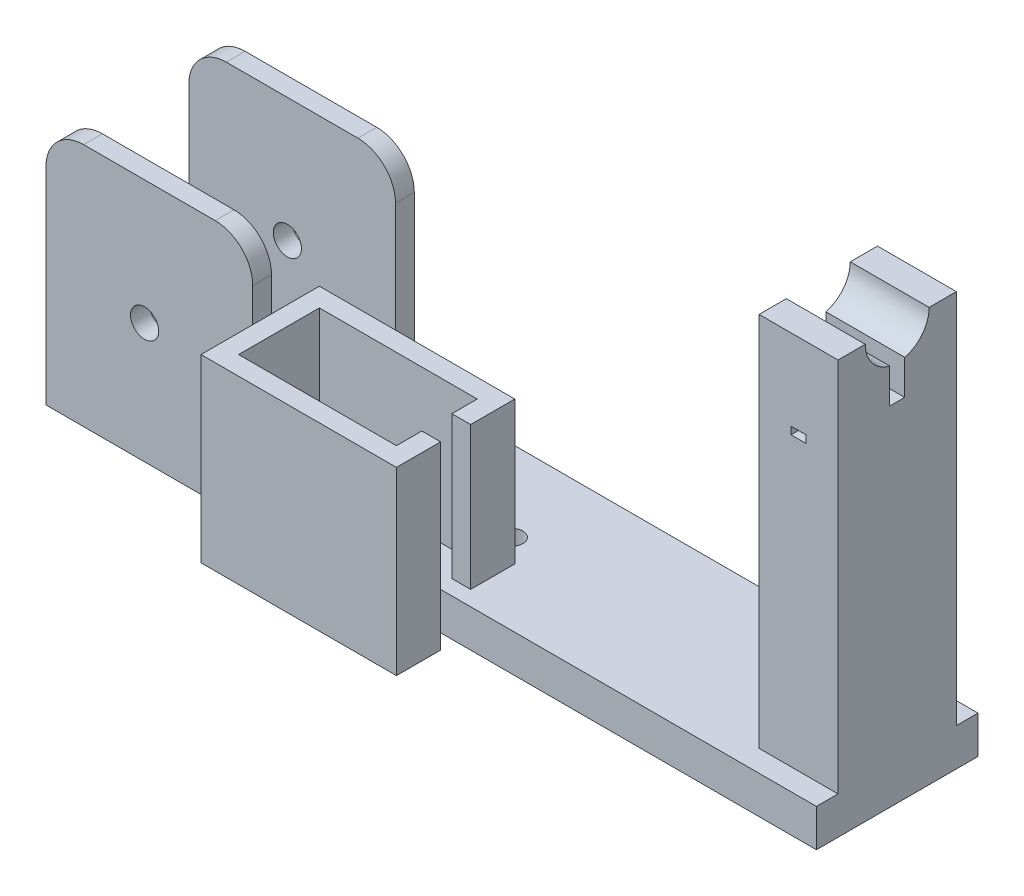
SolidWorks part; units mm, degrees
ref_plane "Front Plane" through (0, 0, 0) normal (0, 0, 1) x (1, 0, 0)
ref_plane "Top Plane" through (0, 0, 0) normal (0, 1, 0) x (1, 0, 0)
ref_plane "Right Plane" through (0, 0, 0) normal (1, 0, 0) x (0, 0, -1)
sketch "Sketch1" plane through (0, 0, 0) normal (0, 1, 0) x (1, 0, 0)
  line L0 (-156.8835, 43.5644) -> (48.1165, 43.5644)
  line L1 (48.1165, 0.5644) -> (-156.8835, 0.5644)
  line L19 (-156.8835, 43.5644) -> (-156.8835, 0.5644)
  line L21 (48.1165, 43.5644) -> (48.1165, 0.5644)
  dimension "D1" = 205
  dimension "D5" = 43
extrude "Boss-Extrude1" add sketch "Sketch1" along normal blind 10
sketch "Sketch2" plane through (0, 0, 0) normal (0, -1, 0) x (1, 0, 0)
  line L0 (-55.6367, -6.8112) -> (-28.1303, -6.8112) construction
  line L1 (-41.8835, -6.8112) -> (-41.8835, -34.3177) construction
  line L2 (-28.1303, -34.3177) -> (-55.6367, -34.3177) construction
  line L3 (-28.1303, -6.8112) -> (-28.1303, -34.3177) construction
  line L4 (-49.4902, -19.0389) -> (-43.4091, -12.9578) construction
  line L5 (-55.6367, -6.8112) -> (-28.1303, -34.3177) construction
  line L6 (-95.1644, -20.5644) -> (-28.1303, -20.5644) construction
  line L7 (-27.868, -10.4768) -> (-34.2768, -19.0389)
  line L8 (-31.7959, -6.5489) -> (-40.358, -12.9578)
  line L9 (-34.2768, -19.0389) -> (-40.358, -12.9578) construction
  line L10 (-55.899, -30.6521) -> (-49.4902, -22.09)
  line L11 (-51.9712, -34.5799) -> (-43.4091, -28.1711)
  line L12 (-51.9712, -6.5489) -> (-43.4091, -12.9578)
  line L13 (-55.899, -10.4768) -> (-49.4902, -19.0389)
  line L14 (-55.6367, -34.3177) -> (-28.1303, -6.8112) construction
  line L15 (-31.7959, -34.5799) -> (-40.358, -28.1711)
  line L16 (-27.868, -30.6521) -> (-34.2768, -22.09)
  line L17 (-156.8835, -0.5644) -> (48.1165, -0.5644) construction
  line L18 (-156.8835, -43.5644) -> (-156.8835, -0.5644) construction
  circle A0 centre (-41.8835, -20.5644) radius 6.75 construction
  arc A1 (-49.4902, -19.0389) -> (-49.4902, -22.09) centre (-50.4202, -20.5644) cw
  arc A2 (-27.868, -30.6521) -> (-31.7959, -34.5799) centre (-30.1144, -32.3335) cw
  arc A3 (-55.899, -10.4768) -> (-51.9712, -6.5489) centre (-53.6526, -8.7953) cw
  arc A4 (-27.868, -10.4768) -> (-31.7959, -6.5489) centre (-30.1144, -8.7953) ccw
  arc A5 (-34.2768, -19.0389) -> (-34.2768, -22.09) centre (-33.3468, -20.5644) ccw
  arc A6 (-55.899, -30.6521) -> (-51.9712, -34.5799) centre (-53.6526, -32.3335) ccw
  arc A7 (-40.358, -28.1711) -> (-43.4091, -28.1711) centre (-41.8835, -29.1011) ccw
  arc A8 (-40.358, -12.9578) -> (-43.4091, -12.9578) centre (-41.8835, -12.0277) cw
  point P6 (-28.1303, -20.5644)
  point P7 (-41.8835, -6.8112)
  dimension "D1" = 19.45
  dimension "D2" = 8.6
  dimension "D3" = 20
  dimension "D4" = 115
extrude "Servo Cutout" [suppressed] cut sketch "Sketch2" against normal blind 3
sketch "Sketch4" plane through (0, 10, 0) normal (0, 1, 0) x (1, 0, 0)
  line L1 (-156.8835, 0.5644) -> (-101.8835, 0.5644)
  line L2 (-156.8835, 0.5644) -> (-156.8835, 5.5644)
  line L3 (-156.8835, 5.5644) -> (-101.8835, 5.5644)
  line L4 (-101.8835, 0.5644) -> (-101.8835, 5.5644)
  dimension "D1" = 55
  dimension "D2" = 5
extrude "Boss-Extrude2" add sketch "Sketch4" along normal blind 55
ref_plane "Plane2" through (0, 0, -22.0644) normal (0, 0, 1) x (1, 0, 0)
mirror "Mirror1" about plane through (0, 0, -22.0644) normal (0, 0, 1) of "Boss-Extrude2"
sketch "Sketch5" plane through (0, 10, 0) normal (0, 1, 0) x (1, 0, 0)
  line L0 (27.1165, 22.0644) -> (48.1165, 22.0644) construction
  line L1 (-35.75, 22.0644) -> (35.75, 22.0644) construction
  line L6 (27.1165, 37.8144) -> (48.1165, 37.8144)
  line L7 (27.1165, 37.8144) -> (27.1165, 6.3144)
  line L13 (27.1165, 6.3144) -> (48.1165, 6.3144)
  line L14 (48.1165, 37.8144) -> (48.1165, 6.3144)
  line L15 (48.1165, 0.5644) -> (48.1165, 43.5644) construction
  point P0 (50.1546, 22.0644)
  dimension "D1" = 0
  dimension "D2" = 0
  dimension "D3" = 21
  dimension "D4" = 31.5
extrude "Barrel Stand" add sketch "Sketch5" along normal blind 100
sketch "Sketch6" plane through (48.1165, 0, 10.3021) normal (-1, 0, 0) x (0, 0, 1)
  line L9 (-32.3665, 110) -> (-32.3665, 93.896) construction
  line L10 (-34.3665, 92.5) -> (-30.3665, 92.5)
  line L11 (-34.3665, 92.5) -> (-34.3665, 101.7386)
  line L13 (-30.3665, 92.5) -> (-30.3665, 101.7386)
  line L14 (-34.3665, 92.5) -> (-32.3665, 101.5) construction
  line L15 (-32.3665, 101.5) -> (-30.3665, 92.5) construction
  line L16 (-16.6165, 110) -> (-48.1165, 110) construction
  arc A3 (-30.3665, 101.7386) -> (-34.3665, 101.7386) centre (-32.3665, 110) ccw
  point P2 (-32.3665, 101.5)
  dimension "D1" = 17
  dimension "D2" = 0
  dimension "D3" = 4
  dimension "D4" = 0
extrude "Cut-Extrude4" cut sketch "Sketch6" along normal up to surface (21 mm away) up to face at (27.1165, 60, -22.0644)
sketch "Sketch7" plane through (0, 0, -0.5644) normal (0, 0, 1) x (1, 0, 0)
  line L0 (-101.8835, 10) -> (48.1165, 10) construction
  circle A0 centre (-130.657, 32) radius 3.75
  dimension "D1" = 22
  dimension "D2" = 7.5
extrude "Bolt Hole" cut sketch "Sketch7" against normal through all
fillet "Fillet3" radius 10 4 edges at (-156.8835, 65, -3.0644) (-156.8835, 65, -41.0644) (-101.8835, 65, -41.0644) (-101.8835, 65, -3.0644)
sketch "Sketch9" [suppressed] plane through (0, 0, 0) normal (0, -1, 0) x (1, 0, 0)
  line L0 (-55.6367, -8.3112) -> (-28.1303, -8.3112) construction
  line L1 (-41.8835, -8.3112) -> (-41.8835, -35.8177) construction
  line L2 (-28.1303, -35.8177) -> (-55.6367, -35.8177) construction
  line L3 (-28.1303, -8.3112) -> (-28.1303, -35.8177) construction
  line L4 (-49.4902, -20.5389) -> (-43.4091, -14.4578) construction
  line L5 (-55.6367, -8.3112) -> (-28.1303, -35.8177) construction
  line L6 (-178.3828, -22.0644) -> (-28.1303, -22.0644) construction
  line L7 (-27.868, -11.9768) -> (-34.2768, -20.5389)
  line L8 (-31.7959, -8.0489) -> (-40.358, -14.4578)
  line L9 (-34.2768, -20.5389) -> (-40.358, -14.4578) construction
  line L10 (-55.899, -32.1521) -> (-49.4902, -23.59)
  line L11 (-51.9712, -36.0799) -> (-43.4091, -29.6711)
  line L12 (-51.9712, -8.0489) -> (-43.4091, -14.4578)
  line L13 (-55.899, -11.9768) -> (-49.4902, -20.5389)
  line L14 (-55.6367, -35.8177) -> (-28.1303, -8.3112) construction
  line L15 (-31.7959, -36.0799) -> (-40.358, -29.6711)
  line L16 (-27.868, -32.1521) -> (-34.2768, -23.59)
  line L19 (35.75, -22.0644) -> (-35.75, -22.0644) construction
  line L20 (-27.7079, -12.0966) -> (-34.1405, -20.6905)
  line L21 (-27.7079, -32.0322) -> (-34.1405, -23.4383)
  line L22 (-31.9157, -36.24) -> (-40.5096, -29.8074)
  line L23 (-51.8513, -36.24) -> (-43.2574, -29.8074)
  line L24 (-56.0591, -32.0322) -> (-49.6265, -23.4383)
  line L25 (-56.0591, -12.0966) -> (-49.6265, -20.6905)
  line L26 (-51.8513, -7.8888) -> (-43.2574, -14.3215)
  line L27 (-31.9157, -7.8888) -> (-40.5096, -14.3215)
  circle A0 centre (-41.8835, -22.0644) radius 6.75 construction
  arc A1 (-49.4902, -20.5389) -> (-49.4902, -23.59) centre (-50.4202, -22.0644) cw
  arc A2 (-27.868, -32.1521) -> (-31.7959, -36.0799) centre (-30.1144, -33.8335) cw
  arc A3 (-55.899, -11.9768) -> (-51.9712, -8.0489) centre (-53.6526, -10.2953) cw
  arc A4 (-27.868, -11.9768) -> (-31.7959, -8.0489) centre (-30.1144, -10.2953) ccw
  arc A5 (-34.2768, -20.5389) -> (-34.2768, -23.59) centre (-33.3468, -22.0644) ccw
  arc A6 (-55.899, -32.1521) -> (-51.9712, -36.0799) centre (-53.6526, -33.8335) ccw
  arc A7 (-40.358, -29.6711) -> (-43.4091, -29.6711) centre (-41.8835, -30.6011) ccw
  arc A8 (-40.358, -14.4578) -> (-43.4091, -14.4578) centre (-41.8835, -13.5277) cw
  arc A9 (-43.4091, -12.9578) -> (-40.358, -12.9578) centre (-41.8835, -12.0277) ccw construction
  arc A10 (-34.1405, -20.6905) -> (-34.1405, -23.4383) centre (-33.3468, -22.0644) ccw
  arc A11 (-27.7079, -32.0322) -> (-31.9157, -36.24) centre (-30.1144, -33.8335) cw
  arc A12 (-40.5096, -29.8074) -> (-43.2574, -29.8074) centre (-41.8835, -30.6011) ccw
  arc A13 (-56.0591, -32.0322) -> (-51.8513, -36.24) centre (-53.6526, -33.8335) ccw
  arc A14 (-49.6265, -20.6905) -> (-49.6265, -23.4383) centre (-50.4202, -22.0644) cw
  arc A15 (-56.0591, -12.0966) -> (-51.8513, -7.8888) centre (-53.6526, -10.2953) cw
  arc A16 (-40.5096, -14.3215) -> (-43.2574, -14.3215) centre (-41.8835, -13.5277) cw
  arc A17 (-27.7079, -12.0966) -> (-31.9157, -7.8888) centre (-30.1144, -10.2953) ccw
  point P6 (-28.1303, -22.0644)
  point P7 (-41.8835, -8.3112)
  dimension "D1" = 19.45
  dimension "D2" = 8.6
  dimension "D3" = 0
  dimension "D4" = 0
  dimension "D5" = 0.2
extrude "Cut-Extrude8" [suppressed] cut sketch "Sketch9" against normal blind 10
ref_plane "Plane3" through (-54.3835, 0, 0) normal (1, 0, 0) x (0, 0, -1)
sketch "Sketch11" plane through (0, 0, 0) normal (0, -1, 0) x (1, 0, 0)
  line L0 (-68.1366, -8.311) -> (-40.6305, -8.311) construction
  line L1 (-54.3835, -8.311) -> (-54.3835, -35.8178) construction
  line L2 (-40.6305, -35.8178) -> (-68.1366, -35.8178) construction
  line L3 (-40.6305, -8.311) -> (-40.6305, -35.8178) construction
  line L4 (-61.9912, -20.5378) -> (-55.91, -14.4567) construction
  line L5 (-68.1366, -8.311) -> (-40.6305, -35.8178) construction
  line L6 (-95.1644, -22.0644) -> (-40.6305, -22.0644) construction
  line L7 (-40.37, -12.0393) -> (-46.7759, -20.5378)
  line L8 (-44.3588, -8.0506) -> (-52.8571, -14.4567)
  line L9 (-46.7759, -20.5378) -> (-52.8571, -14.4567) construction
  line L10 (-68.397, -32.0895) -> (-61.9912, -23.5911)
  line L11 (-64.4082, -36.0782) -> (-55.91, -29.6721)
  line L12 (-64.4082, -8.0506) -> (-55.91, -14.4567)
  line L13 (-68.397, -12.0393) -> (-61.9912, -20.5378)
  line L14 (-68.1366, -35.8178) -> (-40.6305, -8.311) construction
  line L15 (-44.3588, -36.0782) -> (-52.8571, -29.6721)
  line L16 (-40.37, -32.0895) -> (-46.7759, -23.5911)
  line L19 (-54.3835, -23.65) -> (-54.3835, 23.65) construction
  line L20 (35.75, -22.0644) -> (-35.75, -22.0644) construction
  line L25 (-40.2103, -12.1597) -> (-46.6399, -20.6897)
  line L26 (-40.2103, -31.9691) -> (-46.6399, -23.4392)
  line L27 (-44.4792, -36.2379) -> (-53.009, -29.8081)
  line L28 (-64.2878, -36.2379) -> (-55.7581, -29.8081)
  line L29 (-157.0835, -0.3644) -> (-157.0835, -43.7644)
  line L30 (-157.0835, -43.7644) -> (48.3165, -43.7644)
  line L31 (48.3165, -43.7644) -> (48.3165, -0.3644)
  line L32 (48.3165, -0.3644) -> (-157.0835, -0.3644)
  line L33 (-157.0835, -0.3644) -> (-157.0835, -43.7644)
  line L34 (-157.0835, -43.7644) -> (48.3165, -43.7644)
  line L35 (48.3165, -43.7644) -> (48.3165, -0.3644)
  line L36 (48.3165, -0.3644) -> (-157.0835, -0.3644)
  line L37 (-68.5567, -31.9691) -> (-62.1271, -23.4392)
  line L38 (-68.5567, -12.1597) -> (-62.1271, -20.6897)
  line L39 (-64.2878, -7.8909) -> (-55.7581, -14.3208)
  line L40 (-44.4792, -7.8909) -> (-53.009, -14.3208)
  circle A0 centre (-54.3835, -22.0644) radius 6.7498 construction
  arc A1 (-61.9912, -20.5378) -> (-61.9912, -23.5911) centre (-62.9206, -22.0644) cw
  arc A2 (-40.37, -32.0895) -> (-44.3588, -36.0782) centre (-42.6444, -33.8039) cw
  arc A3 (-68.397, -12.0393) -> (-64.4082, -8.0506) centre (-66.1226, -10.325) cw
  arc A4 (-40.37, -12.0393) -> (-44.3588, -8.0506) centre (-42.6444, -10.325) ccw
  arc A5 (-46.7759, -20.5378) -> (-46.7759, -23.5911) centre (-45.8464, -22.0644) ccw
  arc A6 (-68.397, -32.0895) -> (-64.4082, -36.0782) centre (-66.1226, -33.8039) ccw
  arc A7 (-52.8571, -29.6721) -> (-55.91, -29.6721) centre (-54.3835, -30.6011) ccw
  arc A8 (-52.8571, -14.4567) -> (-55.91, -14.4567) centre (-54.3835, -13.5277) cw
  arc A9 (-46.6399, -20.6897) -> (-46.6399, -23.4392) centre (-45.8464, -22.0644) ccw
  arc A10 (-40.2103, -31.9691) -> (-44.4792, -36.2379) centre (-42.6444, -33.8039) cw
  arc A11 (-53.009, -29.8081) -> (-55.7581, -29.8081) centre (-54.3835, -30.6011) ccw
  arc A12 (-68.5567, -31.9691) -> (-64.2878, -36.2379) centre (-66.1226, -33.8039) ccw
  arc A13 (-62.1271, -20.6897) -> (-62.1271, -23.4392) centre (-62.9206, -22.0644) cw
  arc A14 (-68.5567, -12.1597) -> (-64.2878, -7.8909) centre (-66.1226, -10.325) cw
  arc A15 (-53.009, -14.3208) -> (-55.7581, -14.3208) centre (-54.3835, -13.5277) cw
  arc A16 (-40.2103, -12.1597) -> (-44.4792, -7.8909) centre (-42.6444, -10.325) ccw
  point P6 (-40.6305, -22.0644)
  point P7 (-54.3835, -8.311)
  dimension "D1" = 19.45
  dimension "D2" = 8.6
  dimension "D3" = 0
  dimension "D4" = 0
  dimension "D5" = 0.2
  dimension "D6" = 0.2
extrude "Cut-Extrude9" cut sketch "Sketch11" against normal blind 2.8 contours L8 A8 L12 A3 L13 A1 L10 A6 L11 A7 L15 A2 L16 A5 L7 A4 | L25 A16 L40 A15 L39 A14 L38 A13 L37 A12 L28 A11 L27 A10 L26 A9 A8 L8 A4 L7 A5 L16 A2 L15 A7 L11 A6 L10 A1 L13 A3 L12
sketch "Sketch12" plane through (0, 10, 0) normal (0, 1, 0) x (1, 0, 0)
  line L0 (-54.3835, -23.65) -> (-54.3835, 23.65) construction
  line L1 (-35.75, 22.0644) -> (35.75, 22.0644) construction
  circle A0 centre (-54.3835, 22.0644) radius 2.9
  dimension "D1" = 0
  dimension "D2" = 5.8
extrude "Cut-Extrude10" cut sketch "Sketch12" against normal blind 10
sketch "Sketch13" plane through (0, 0, -6.3144) normal (0, 0, 1) x (1, 0, 0)
  line L0 (37.6165, 110) -> (37.6165, 68.0082) construction
  line L1 (27.1165, 110) -> (48.1165, 110) construction
  line L2 (27.1165, 92.5) -> (48.1165, 92.5) construction
  line L3 (35.6165, 86.5) -> (39.6165, 86.5)
  line L4 (35.6165, 86.5) -> (35.6165, 88.5)
  line L5 (35.6165, 88.5) -> (39.6165, 88.5)
  line L6 (39.6165, 86.5) -> (39.6165, 88.5)
  line L7 (35.6165, 86.5) -> (39.6165, 88.5) construction
  line L8 (35.6165, 88.5) -> (39.6165, 86.5) construction
  point P4 (37.6165, 87.5)
  dimension "D1" = 4
  dimension "D2" = 2
  dimension "D3" = 4
extrude "Zip Tie Slot" cut sketch "Sketch13" against normal through all
sketch "Sketch14" plane through (0, 10, 0) normal (0, 1, 0) x (1, 0, 0)
  line L0 (-101.8835, 0.5644) -> (48.1165, 0.5644) construction
  line L1 (-94.8835, -10.1856) -> (-52.8835, -10.1856)
  line L2 (-94.8835, -10.1856) -> (-94.8835, 11.3144)
  line L3 (-94.8835, 11.3144) -> (-52.8835, 11.3144)
  line L4 (-52.8835, -10.1856) -> (-52.8835, -3.4356)
  line L5 (-94.8835, -10.1856) -> (-52.8835, 11.3144) construction
  line L6 (-94.8835, 11.3144) -> (-52.8835, -10.1856) construction
  line L7 (-52.8835, 4.5644) -> (-47.8835, 4.5644)
  line L8 (-99.8835, -15.1856) -> (-99.8835, 16.3144)
  line L9 (-99.8835, 16.3144) -> (-47.8835, 16.3144)
  line L10 (-47.8835, -15.1856) -> (-47.8835, -3.4356)
  line L11 (-99.8835, -15.1856) -> (-47.8835, -15.1856)
  line L12 (-101.8835, 0.5644) -> (-101.8835, 5.5644) construction
  line L13 (-52.8835, -3.4356) -> (-47.8835, -3.4356)
  line L21 (-52.8835, 4.5644) -> (-52.8835, 11.3144)
  line L22 (-52.8835, -10.1856) -> (-52.8835, 11.3144) construction
  line L23 (-47.8835, 4.5644) -> (-47.8835, 16.3144)
  line L24 (-47.8835, -15.1856) -> (-47.8835, 16.3144) construction
  point P0 (-73.8835, 0.5644)
  point P13 (-52.8835, 0.5644)
  dimension "D1" = 5
  dimension "D2" = 42
  dimension "D3" = 21.5
  dimension "D4" = 7
extrude "Boss-Extrude3" add sketch "Sketch14" along normal blind 38
sketch "Sketch15" plane through (0, 10, 0) normal (0, -1, 0) x (1, 0, 0)
  line L9 (-52.8835, 10.1856) -> (-94.8835, 10.1856) construction
  line L10 (-47.8835, 15.1856) -> (-99.8835, 15.1856)
  line L11 (-47.8835, 15.1856) -> (-47.8835, 3.4356)
  line L13 (-99.8835, 15.1856) -> (-99.8835, -0.5644)
  line L15 (-94.8835, -0.5644) -> (-94.8835, 10.1856)
  line L16 (-94.8835, 10.1856) -> (-52.8835, 10.1856)
  line L17 (-52.8835, 3.4356) -> (-52.8835, 10.1856)
  line L18 (-94.8835, -0.5644) -> (-99.8835, -0.5644)
  line L19 (-47.8835, 3.4356) -> (-52.8835, 3.4356)
extrude "Boss-Extrude4" add sketch "Sketch15" along normal up to surface (10 mm away) up to face at (-54.3835, 0, -22.0644)
